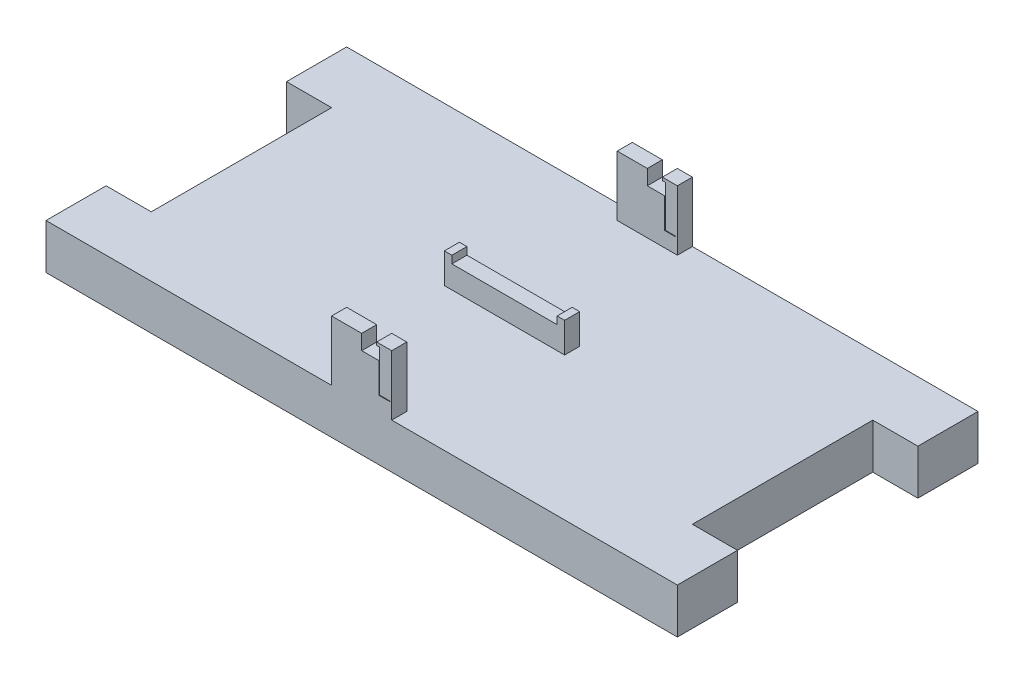
SolidWorks part; units mm, degrees
material "6061 Alloy"
ref_plane "Front Plane" through (0, 0, 0) normal (0, 0, 1) x (1, 0, 0)
ref_plane "Top Plane" through (0, 0, 0) normal (0, 1, 0) x (1, 0, 0)
ref_plane "Right Plane" through (0, 0, 0) normal (1, 0, 0) x (0, 0, -1)
sketch "Sketch1" plane through (0, 0, 0) normal (0, 1, 0) x (1, 0, 0)
  line L1 (-133.35, -63.5) -> (133.35, -63.5)
  line L2 (-133.35, -63.5) -> (-133.35, 63.5)
  line L3 (-133.35, 63.5) -> (133.35, 63.5)
  line L4 (133.35, -63.5) -> (133.35, 63.5)
  line L5 (-133.35, -63.5) -> (133.35, 63.5) construction
  line L6 (-133.35, 63.5) -> (133.35, -63.5) construction
  point P0 (0, 0)
  dimension "D1" = 266.7
  dimension "D2" = 127
extrude "Boss-Extrude1" add sketch "Sketch1" along normal blind 19.05
sketch "Sketch2" plane through (0, 19.05, 0) normal (0, 1, 0) x (1, 0, 0)
  line L0 (-133.35, 63.5) -> (-133.35, -63.5) construction
  line L1 (-133.35, 38.1) -> (-114.3, 38.1)
  line L2 (-133.35, 38.1) -> (-133.35, -38.1)
  line L3 (-133.35, -38.1) -> (-114.3, -38.1)
  line L4 (-114.3, 38.1) -> (-114.3, -38.1)
  line L5 (-133.35, -63.5) -> (133.35, -63.5) construction
  line L6 (133.35, 63.5) -> (-133.35, 63.5) construction
  dimension "D1" = 25.4
  dimension "D2" = 25.4
  dimension "D3" = 19.05
extrude "Cut-Extrude1" cut sketch "Sketch2" against normal through all
mirror "Mirror1" about plane through (0, 0, 0) normal (1, 0, 0) of "Cut-Extrude1"
sketch "Sketch3" plane through (0, 19.05, 0) normal (0, 1, 0) x (1, 0, 0)
  line L0 (-133.35, -63.5) -> (133.35, -63.5) construction
  line L1 (-12.7, -57.15) -> (12.7, -57.15)
  line L2 (-12.7, -57.15) -> (-12.7, -63.5)
  line L3 (-12.7, -63.5) -> (12.7, -63.5)
  line L4 (12.7, -57.15) -> (12.7, -63.5)
  line L5 (-12.7, -57.15) -> (12.7, -63.5) construction
  line L6 (-12.7, -63.5) -> (12.7, -57.15) construction
  point P0 (0, -60.325)
  dimension "D1" = 6.35
  dimension "D2" = 25.4
  dimension "D3" = 12.7
extrude "Boss-Extrude2" add sketch "Sketch3" along normal blind 25.4
sketch "Sketch5" plane through (0, 0, 63.5) normal (0, 0, 1) x (1, 0, 0)
  line L0 (-12.7, 44.45) -> (12.7, 44.45) construction
  line L1 (0, 38.1) -> (6.35, 38.1)
  line L2 (0, 38.1) -> (0, 44.45)
  line L3 (0, 44.45) -> (6.35, 44.45)
  line L4 (6.35, 38.1) -> (6.35, 44.45)
  line L5 (0, 38.1) -> (6.35, 44.45) construction
  line L6 (0, 44.45) -> (6.35, 38.1) construction
  line L7 (12.7, 44.45) -> (12.7, 19.05) construction
  point P0 (3.175, 41.275)
  dimension "D1" = 6.35
  dimension "D2" = 6.35
  dimension "D3" = 6.35
extrude "Cut-Extrude2" cut sketch "Sketch5" against normal through all
sketch "Sketch6" plane through (0, 0, 63.5) normal (0, 0, 1) x (1, 0, 0)
  line L1 (6.35, 38.1) -> (7.62, 38.1)
  line L2 (6.35, 38.1) -> (6.35, 43.18)
  line L3 (6.35, 43.18) -> (7.62, 43.18)
  line L4 (7.62, 38.1) -> (7.62, 43.18)
  dimension "D1" = 1.27
  dimension "D2" = 5.08
extrude "Cut-Extrude3" cut sketch "Sketch6" against normal through all
sketch "Sketch7" plane through (0, 0, 63.5) normal (0, 0, 1) x (1, 0, 0)
  line L0 (12.7, 44.45) -> (12.7, 19.05) construction
  line L1 (7.62, 38.1) -> (7.366, 38.1)
  line L2 (7.62, 38.1) -> (7.62, 25.4)
  line L3 (7.62, 25.4) -> (7.366, 25.4)
  line L4 (7.366, 38.1) -> (7.366, 25.4)
  line L5 (7.366, 25.4) -> (11.938, 25.4)
  line L6 (7.366, 25.4) -> (7.366, 25.654)
  line L7 (7.366, 25.654) -> (11.938, 25.654)
  line L8 (11.938, 25.4) -> (11.938, 25.654)
  point P8 (11.938, 25.527)
  dimension "D1" = 0.762
  dimension "D2" = 0.254
  dimension "D3" = 0.254
  dimension "D4" = 12.7
extrude "Cut-Extrude4" cut sketch "Sketch7" against normal through all contours L6 L7 L8 L5 | L3 L2 L1 L4
mirror "Mirror2" about plane through (0, 0, 0) normal (0, 0, 1) of "Cut-Extrude2", "Cut-Extrude3", "Cut-Extrude4", "Boss-Extrude2"
sketch "Sketch8" plane through (0, 19.05, 0) normal (0, 1, 0) x (1, 0, 0)
  line L1 (-25.4, -3.175) -> (25.4, -3.175)
  line L2 (-25.4, -3.175) -> (-25.4, 3.175)
  line L3 (-25.4, 3.175) -> (25.4, 3.175)
  line L4 (25.4, -3.175) -> (25.4, 3.175)
  line L5 (-25.4, -3.175) -> (25.4, 3.175) construction
  line L6 (-25.4, 3.175) -> (25.4, -3.175) construction
  point P0 (0, 0)
  dimension "D1" = 50.8
  dimension "D2" = 6.35
extrude "Boss-Extrude3" add sketch "Sketch8" along normal blind 12.7
sketch "Sketch9" plane through (0, 0, 3.175) normal (0, 0, 1) x (1, 0, 0)
  line L0 (-25.4, 31.75) -> (25.4, 31.75) construction
  line L1 (-22.225, 34.925) -> (22.225, 34.925)
  line L2 (-22.225, 34.925) -> (-22.225, 28.575)
  line L3 (-22.225, 28.575) -> (22.225, 28.575)
  line L4 (22.225, 34.925) -> (22.225, 28.575)
  line L5 (-22.225, 34.925) -> (22.225, 28.575) construction
  line L6 (-22.225, 28.575) -> (22.225, 34.925) construction
  point P0 (0, 31.75)
  dimension "D1" = 3.175
  dimension "D2" = 44.45
extrude "Cut-Extrude5" cut sketch "Sketch9" against normal up to next
